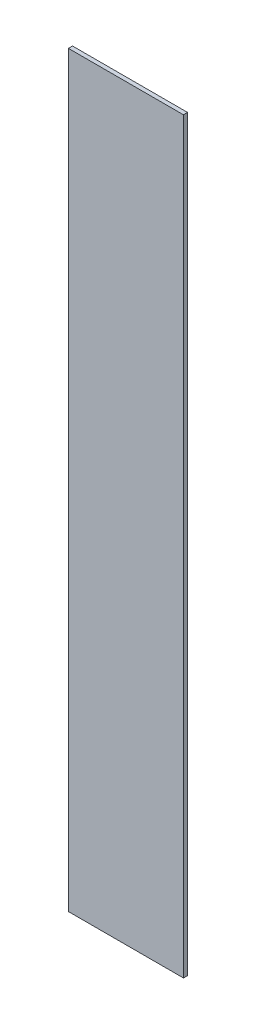
SolidWorks part; units mm, degrees
ref_plane "Front Plane" through (0, 0, 0) normal (0, 0, 1) x (1, 0, 0)
ref_plane "Top Plane" through (0, 0, 0) normal (0, 1, 0) x (1, 0, 0)
ref_plane "Right Plane" through (0, 0, 0) normal (1, 0, 0) x (0, 0, -1)
other "Configuration Table"
sketch "Sketch1" plane through (0, 0, 0) normal (0, 0, 1) x (1, 0, 0)
  line L1 (623, 129) -> (651, 129)
  line L2 (623, 129) -> (623, 311)
  line L3 (623, 311) -> (651, 311)
  line L4 (651, 129) -> (651, 311)
extrude "OVEN_pano_kapagi_kulp_cukuru_1" add sketch "Sketch1" along normal blind 1 from offset 26 separate body
